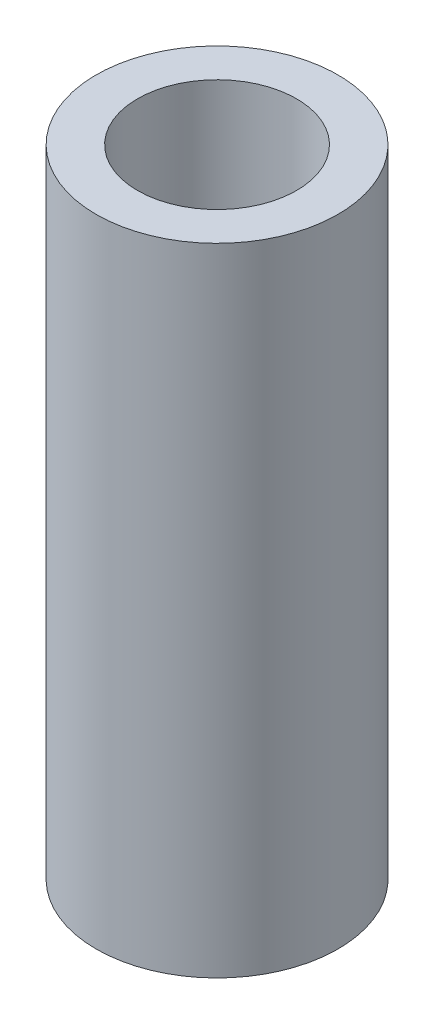
SolidWorks part; units mm, degrees
material "Alloy Steel"
ref_plane "Front Plane" through (0, 0, 0) normal (0, 0, 1) x (1, 0, 0)
ref_plane "Top Plane" through (0, 0, 0) normal (0, 1, 0) x (1, 0, 0)
ref_plane "Right Plane" through (0, 0, 0) normal (1, 0, 0) x (0, 0, -1)
sketch "Sketch1" plane through (0, 0, 0) normal (0, 1, 0) x (1, 0, 0)
  circle A0 centre (0, 0) radius 9.5
  circle A1 centre (0, 0) radius 6.25
  dimension "D1" = 12.5
  dimension "D2" = 19
extrude "Boss-Extrude1" add sketch "Sketch1" along normal blind 50
